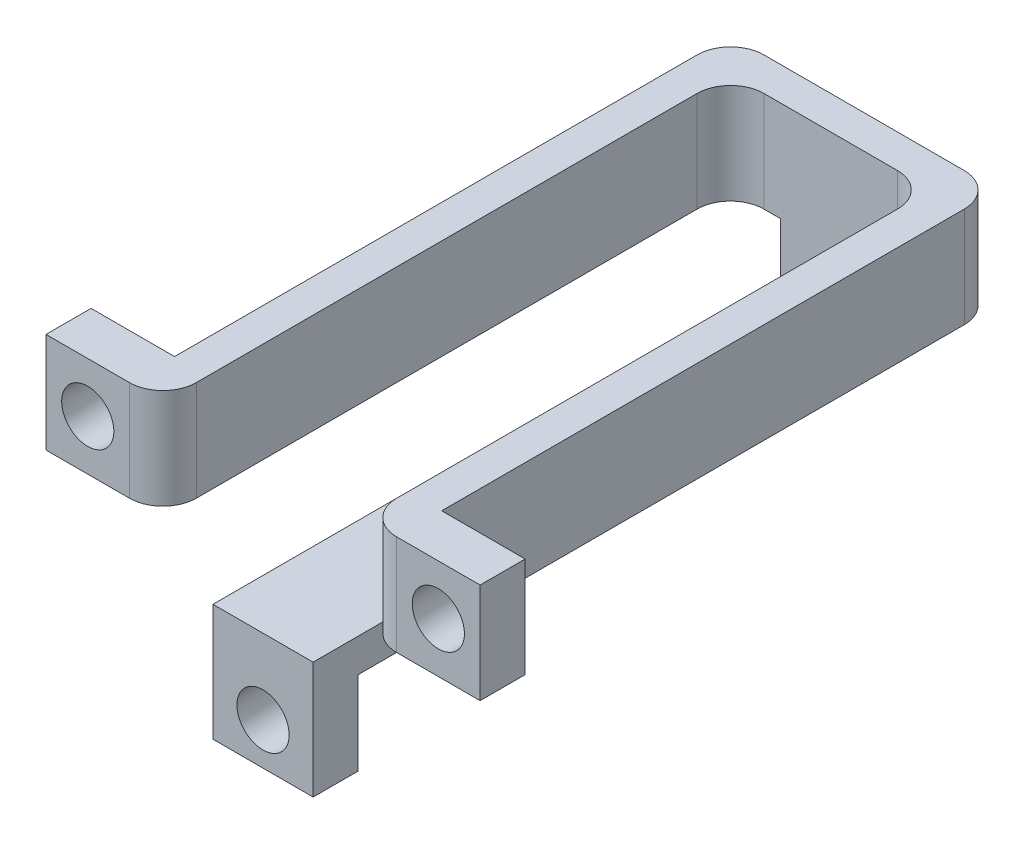
SolidWorks part; units mm, degrees
ref_plane "Front Plane" through (0, 0, 0) normal (0, 0, 1) x (1, 0, 0)
ref_plane "Top Plane" through (0, 0, 0) normal (0, 1, 0) x (1, 0, 0)
ref_plane "Right Plane" through (0, 0, 0) normal (1, 0, 0) x (0, 0, -1)
sketch "Sketch2" plane through (0, 0, 0) normal (0, 1, 0) x (1, 0, 0)
  line L0 (-101.6, -215.9) -> (-101.6, 241.3)
  line L2 (-76.2, -215.9) -> (-76.2, 215.9)
  line L3 (-76.2, 215.9) -> (76.2, 215.9)
  line L4 (76.2, -215.9) -> (76.2, 215.9)
  line L5 (-76.2, -215.9) -> (76.2, 215.9) construction
  line L6 (-76.2, 215.9) -> (76.2, -215.9) construction
  line L7 (-101.6, 241.3) -> (101.6, 241.3)
  line L8 (101.6, -215.9) -> (101.6, 241.3)
  line L9 (-101.6, -215.9) -> (-76.2, -215.9)
  line L10 (101.6, -215.9) -> (76.2, -215.9)
  point P0 (0, 0)
  dimension "D1" = 152.4
  dimension "D2" = 431.8
  dimension "D3" = 25.4
extrude "Boss-Extrude1" add sketch "Sketch2" along normal blind 76.2
sketch "Sketch3" plane through (101.6, 0, 0) normal (1, 0, 0) x (0, 0, -1)
  line L0 (-215.9, 0) -> (241.3, 0) construction
  line L1 (-215.9, 76.2) -> (-181.61, 76.2)
  line L2 (-215.9, 76.2) -> (-215.9, 0)
  line L3 (-215.9, 0) -> (-181.61, 0)
  line L4 (-181.61, 76.2) -> (-181.61, 0)
  dimension "D1" = 34.29
extrude "Boss-Extrude2" add sketch "Sketch3" along normal blind 63.5
mirror "Mirror1" about plane through (0, 0, 0) normal (1, 0, 0) of "Boss-Extrude2"
fillet "Fillet1" radius 25.4 4 edges at (101.6, 38.1, -241.3) (-101.6, 38.1, -241.3) (-76.2, 38.1, 215.9) (76.2, 38.1, 215.9)
fillet "Fillet2" radius 25.4 2 edges at (-76.2, 38.1, -215.9) (76.2, 38.1, -215.9)
hole_wizard "1-3/4-5 Tapped Hole1" positions "Sketch6" profile "Sketch5" tap size "1-3/4-5" standard "ANSI Inch" end condition up to next
sketch "Sketch6" plane through (0, 0, 181.61) normal (0, 0, -1) x (-1, 0, 0)
  line L0 (-165.1, 76.2) -> (-101.6, 76.2) construction
  line L1 (-101.6, 0) -> (-101.6, 76.2) construction
  point P0 (-133.35, 38.1)
  dimension "D1" = 38.1
  dimension "D2" = 31.75
sketch "Sketch5" plane through (133.35, 38.1, 181.61) normal (1, 0, 0) x (0, 1, 0)
  line L0 (0, 0) -> (0, 34.291)
  line L1 (0, 34.291) -> (19.8437, 34.291)
  line L2 (19.8437, 34.291) -> (19.8437, 0)
  line L5 (19.8437, 0) -> (0, 0)
  line L11 (0, -6.35) -> (0, 107.95) construction
  dimension "Thru Tap Drill Dia." = 39.6875
  dimension "Thru Tap Drill Depth" = 34.291
cosmetic thread "Hole Thread1" parameters "D2"=44.45
mirror "Mirror2" about plane through (0, 0, 0) normal (1, 0, 0) of "1-3/4-5 Tapped Hole1"
ref_plane "Plane1" through (0, 0, 215.9) normal (0, 0, 1) x (1, 0, 0)
sketch "Sketch9" plane through (0, 0, 0) normal (1, 0, 0) x (0, 0, -1)
  line L0 (-215.9, 34.925) -> (-215.9, -34.925) construction
  line L1 (-215.9, -63.5) -> (241.3, -63.5)
  line L2 (-215.9, -63.5) -> (-215.9, -38.1)
  line L4 (241.3, -63.5) -> (241.3, 38.1)
  line L5 (-215.9, -38.1) -> (215.9, -38.1)
  line L6 (215.9, -38.1) -> (215.9, 38.1)
  line L9 (-181.61, 38.1) -> (462.9679, 38.1) construction
  line L10 (-181.61, 0) -> (-181.61, 76.2) construction
  line L12 (241.3, 38.1) -> (215.9, 38.1)
  dimension "D1" = 101.6
  dimension "D2" = 457.2
  dimension "D3" = 25.4
  dimension "D4" = 25.4
extrude "Boss-Extrude3" add sketch "Sketch9" along normal mid plane 76.2
sketch "Sketch10" plane through (0, -63.5, 0) normal (0, -1, 0) x (1, 0, 0)
  line L0 (-38.1, 215.9) -> (-38.1, -241.3) construction
  line L1 (38.1, 215.9) -> (-38.1, 215.9)
  line L2 (38.1, 215.9) -> (38.1, 181.61)
  line L3 (38.1, 181.61) -> (-38.1, 181.61)
  line L4 (-38.1, 215.9) -> (-38.1, 181.61)
  dimension "D1" = 34.29
extrude "Boss-Extrude4" add sketch "Sketch10" along normal blind 63.5
hole_wizard "1-3/4-5 Tapped Hole2" positions "Sketch11" profile "Sketch12" tap size "1-3/4-5" standard "ANSI Inch" end condition through all
sketch "Sketch11" plane through (0, 0, 181.61) normal (0, 0, -1) x (-1, 0, 0)
  line L0 (38.1, -127) -> (38.1, -63.5) construction
  line L1 (38.1, -127) -> (-38.1, -127) construction
  point P0 (0, -95.2213)
  dimension "D1" = 38.1
  dimension "D2" = 31.7787
sketch "Sketch12" plane through (0, -95.2213, 181.61) normal (1, 0, 0) x (0, 1, 0)
  line L0 (0, 0) -> (0, 34.29)
  line L1 (0, 34.29) -> (19.8438, 34.29)
  line L2 (19.8438, 34.29) -> (19.8438, 3.0162)
  line L3 (19.8438, 3.0162) -> (22.86, 0)
  line L5 (22.86, 0) -> (0, 0)
  line L6 (-19.8438, 3.0162) -> (-22.86, 0) construction
  line L11 (0, -6.35) -> (0, 107.95) construction
  dimension "Thru Tap Drill Dia." = 39.6875
  dimension "Thru Tap Drill Depth" = 34.29
  dimension "Near C'Sink Dia." = 45.72
  dimension "Near C'Sink Angle" = 90
cosmetic thread "Hole Thread2" parameters "D2"=44.45
